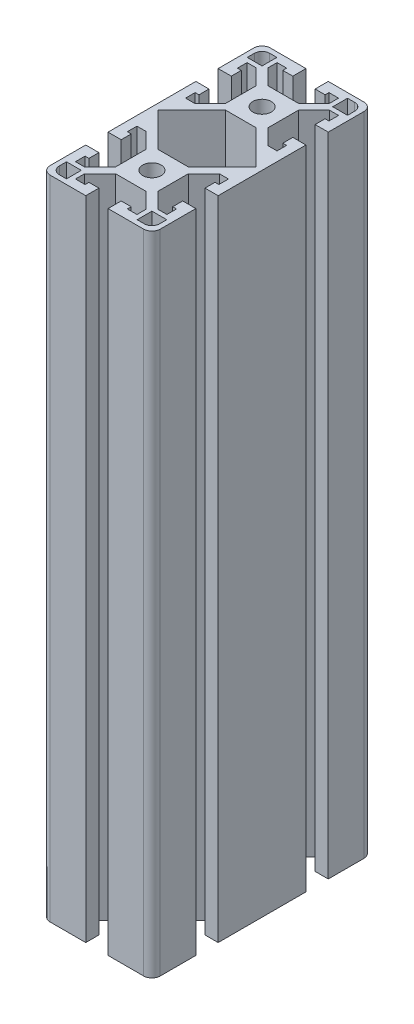
SolidWorks part; units mm, degrees
material "6063-T6"
ref_plane "Front Plane" through (0, 0, 0) normal (0, 0, 1) x (1, 0, 0)
ref_plane "Top Plane" through (0, 0, 0) normal (0, 1, 0) x (1, 0, 0)
ref_plane "Right Plane" through (0, 0, 0) normal (1, 0, 0) x (0, 0, -1)
sketch "Sketch1" plane through (0, 0, 0) normal (0, 0, 1) x (1, 0, 0)
  line L0 (0, 0) -> (0, 235)
  dimension "D1" = 235
other "40 series TS40-80LM-650037(1)"
ref_plane "Plane1" through (0, 0, 0) normal (0, 1, 0) x (-1, 0, 0)
sketch "Sketch2" plane through (0, 0, 0) normal (0, 1, 0) x (-1, 0, 0)
  line L2 (0, -27.681) -> (-5.5257, -27.681)
  line L3 (-5.5257, -27.681) -> (-11.176, -33.3313)
  line L4 (-7.6835, -36.6218) -> (-11.176, -36.6218)
  line L5 (-20, -37) -> (-20, -24.0488)
  line L6 (-4.0488, -40) -> (-17, -40)
  line L7 (-7.681, -20) -> (-7.681, -25.5257)
  line L8 (-7.681, -25.5257) -> (-13.3313, -31.176)
  line L9 (-16.6218, -31.176) -> (-16.6218, -27.6835)
  line L10 (-7.681, -14.4743) -> (-13.3313, -8.824)
  line L11 (-13.3313, -8.824) -> (-16.6218, -8.824)
  line L12 (-20, -24.0488) -> (-15.2248, -24.0488)
  line L13 (-20, 15.9512) -> (-20, -15.9512)
  line L14 (-5.5257, 12.319) -> (-17.8447, 0)
  line L15 (-5.5257, -12.319) -> (-17.8447, 0)
  line L16 (-7.681, -20) -> (-7.681, -14.4743)
  line L17 (-5.5257, -12.319) -> (0, -12.319)
  line L18 (7.681, -20) -> (7.681, -14.4743)
  line L19 (5.5257, -12.319) -> (17.8447, 0)
  line L20 (20, 15.9512) -> (15.2248, 15.9512)
  line L21 (4.0488, -35.2248) -> (7.6835, -35.2248)
  line L22 (7.681, 14.4743) -> (13.3313, 8.824)
  line L23 (7.6835, -36.6218) -> (7.6835, -35.2248)
  line L24 (4.0488, -35.2248) -> (4.0488, -40)
  line L25 (7.6835, -36.6218) -> (11.176, -36.6218)
  line L26 (11.176, -33.3313) -> (11.176, -36.6218)
  line L27 (7.681, -20) -> (7.681, -25.5257)
  line L28 (4.0488, -40) -> (17, -40)
  line L29 (20, -37) -> (20, -24.0488)
  line L30 (5.5257, -27.681) -> (11.176, -33.3313)
  line L31 (7.681, -25.5257) -> (13.3313, -31.176)
  line L32 (0, -12.319) -> (5.5257, -12.319)
  line L33 (0, -27.681) -> (5.5257, -27.681)
  line L35 (13.3313, 8.824) -> (16.6218, 8.824)
  line L36 (0, 12.319) -> (5.5257, 12.319)
  line L37 (-5.5257, 12.319) -> (0, 12.319)
  line L38 (16.6218, 8.824) -> (16.6218, 12.3165)
  line L39 (15.2248, 15.9512) -> (15.2248, 12.3165)
  line L40 (16.6218, 12.3165) -> (15.2248, 12.3165)
  line L41 (20, 24.0488) -> (15.2248, 24.0488)
  line L42 (0, 27.681) -> (5.5257, 27.681)
  line L43 (-4.0488, 40) -> (-17, 40)
  line L44 (-20, 37) -> (-20, 24.0488)
  line L45 (4.0488, 35.2248) -> (4.0488, 40)
  line L46 (16.6218, 31.176) -> (16.6218, 27.6835)
  line L47 (7.681, 20) -> (7.681, 25.5257)
  line L48 (13.3313, 31.176) -> (16.6218, 31.176)
  line L49 (15.2248, 24.0488) -> (15.2248, 27.6835)
  line L50 (7.681, 20) -> (7.681, 14.4743)
  line L51 (-7.681, 25.5257) -> (-7.681, 14.4743)
  line L52 (16.6218, 27.6835) -> (15.2248, 27.6835)
  line L53 (12.8372, 38.222) -> (12.8372, 32.8372)
  line L54 (20, 37) -> (20, 24.0488)
  line L55 (4.0488, 40) -> (17, 40)
  line L56 (12.8372, 38.222) -> (15.428, 38.222)
  line L57 (18.222, 35.428) -> (18.222, 32.8372)
  line L58 (12.8372, 32.8372) -> (18.222, 32.8372)
  line L59 (0, 27.681) -> (-5.5257, 27.681)
  line L60 (-4.0488, -35.2248) -> (-4.0488, -40)
  line L61 (-16.6218, -8.824) -> (-16.6218, -12.3165)
  line L62 (7.681, -14.4743) -> (13.3313, -8.824)
  line L63 (12.8372, -32.8372) -> (18.222, -32.8372)
  line L64 (20, 15.9512) -> (20, -15.9512)
  line L65 (7.681, 25.5257) -> (13.3313, 31.176)
  line L66 (5.5257, 27.681) -> (11.176, 33.3313)
  line L67 (5.5257, 12.319) -> (17.8447, 0)
  line L68 (-13.3313, -31.176) -> (-16.6218, -31.176)
  line L69 (-11.176, -33.3313) -> (-11.176, -36.6218)
  line L70 (-15.2248, -15.9512) -> (-15.2248, -12.3165)
  line L71 (-12.8372, -38.222) -> (-12.8372, -32.8372)
  line L72 (-12.8372, -38.222) -> (-15.428, -38.222)
  line L73 (-15.2248, -24.0488) -> (-15.2248, -27.6835)
  line L74 (-16.6218, -27.6835) -> (-15.2248, -27.6835)
  line L75 (-18.222, -35.428) -> (-18.222, -32.8372)
  line L76 (-12.8372, -32.8372) -> (-18.222, -32.8372)
  line L77 (-7.6835, -36.6218) -> (-7.6835, -35.2248)
  line L78 (-4.0488, -35.2248) -> (-7.6835, -35.2248)
  line L79 (-20, -15.9512) -> (-15.2248, -15.9512)
  line L80 (-16.6218, -12.3165) -> (-15.2248, -12.3165)
  line L81 (18.222, -35.428) -> (18.222, -32.8372)
  line L82 (12.8372, -38.222) -> (15.428, -38.222)
  line L83 (12.8372, -38.222) -> (12.8372, -32.8372)
  line L84 (16.6218, -12.3165) -> (15.2248, -12.3165)
  line L85 (20, -15.9512) -> (15.2248, -15.9512)
  line L86 (16.6218, -27.6835) -> (15.2248, -27.6835)
  line L87 (15.2248, -24.0488) -> (15.2248, -27.6835)
  line L88 (15.2248, -15.9512) -> (15.2248, -12.3165)
  line L89 (13.3313, -31.176) -> (16.6218, -31.176)
  line L90 (16.6218, -8.824) -> (16.6218, -12.3165)
  line L91 (20, -24.0488) -> (15.2248, -24.0488)
  line L92 (13.3313, -8.824) -> (16.6218, -8.824)
  line L93 (16.6218, -31.176) -> (16.6218, -27.6835)
  line L94 (11.176, 33.3313) -> (11.176, 36.6218)
  line L95 (7.6835, 36.6218) -> (11.176, 36.6218)
  line L96 (7.6835, 36.6218) -> (7.6835, 35.2248)
  line L97 (4.0488, 35.2248) -> (7.6835, 35.2248)
  line L98 (-4.0488, 35.2248) -> (-4.0488, 40)
  line L99 (-4.0488, 35.2248) -> (-7.6835, 35.2248)
  line L100 (-7.6835, 36.6218) -> (-7.6835, 35.2248)
  line L101 (-7.6835, 36.6218) -> (-11.176, 36.6218)
  line L102 (-11.176, 33.3313) -> (-11.176, 36.6218)
  line L103 (-5.5257, 27.681) -> (-11.176, 33.3313)
  line L104 (-18.222, 35.428) -> (-18.222, 32.8372)
  line L105 (-12.8372, 32.8372) -> (-18.222, 32.8372)
  line L106 (-7.681, 25.5257) -> (-13.3313, 31.176)
  line L107 (-13.3313, 31.176) -> (-16.6218, 31.176)
  line L108 (-16.6218, 31.176) -> (-16.6218, 27.6835)
  line L109 (-7.681, 14.4743) -> (-13.3313, 8.824)
  line L110 (-16.6218, 12.3165) -> (-15.2248, 12.3165)
  line L111 (-20, 15.9512) -> (-15.2248, 15.9512)
  line L112 (-15.2248, 15.9512) -> (-15.2248, 12.3165)
  line L113 (-16.6218, 8.824) -> (-16.6218, 12.3165)
  line L114 (-13.3313, 8.824) -> (-16.6218, 8.824)
  line L115 (-16.6218, 27.6835) -> (-15.2248, 27.6835)
  line L116 (-15.2248, 24.0488) -> (-15.2248, 27.6835)
  line L117 (-20, 24.0488) -> (-15.2248, 24.0488)
  line L118 (-12.8372, 38.222) -> (-15.428, 38.222)
  line L119 (-12.8372, 38.222) -> (-12.8372, 32.8372)
  arc A0 (-20, -37) -> (-17, -40) centre (-17, -37) ccw
  arc A1 (-20, 37) -> (-17, 40) centre (-17, 37) cw
  arc A2 (20, 37) -> (17, 40) centre (17, 37) ccw
  arc A3 (-15.428, -38.222) -> (-18.222, -35.428) centre (-15.428, -35.428) cw
  arc A4 (15.428, -38.222) -> (18.222, -35.428) centre (15.428, -35.428) ccw
  arc A5 (15.428, 38.222) -> (18.222, 35.428) centre (15.428, 35.428) cw
  arc A6 (-15.428, 38.222) -> (-18.222, 35.428) centre (-15.428, 35.428) ccw
  arc A7 (20, -37) -> (17, -40) centre (17, -37) cw
  circle A8 centre (0, -20) radius 3.35
  circle A9 centre (0, 20) radius 3.35
  point P1 (-20, 20)
  point P3 (-20, 40)
  point P34 (-20, 0)
  point P51 (20, 0)
  point P76 (0, 40)
  point P77 (20, 40)
  point P143 (20, 20)
  point P144 (20, -20)
  point P145 (-20, -20)
  point P146 (-20, -40)
  point P147 (0, -40)
  point P148 (20, -40)
  point P149 (0, 0)
  dimension "D1" = 6.7
hole_wizard "M8x1.25 Tapped Hole1" positions "Sketch3" profile "Sketch4" tap size "M8x1.25" standard "ANSI Metric"
sketch "Sketch3" plane through (0, 0, 0) normal (0, -1, 0) x (-1, 0, 0)
  point P0 (0, -20)
  point P3 (0, 20)
sketch "Sketch4" plane through (0, 0, 20) normal (1, 0, 0) x (0, 0, -1)
  line L0 (0, 0) -> (0, 27.0429)
  line L1 (0, 27.0429) -> (3.4, 25)
  line L2 (3.4, 25) -> (3.4, 0)
  line L5 (3.4, 0) -> (0, 0)
  line L10 (0, 27.0429) -> (-3.4, 25) construction
  line L11 (0, -6.35) -> (0, 107.95) construction
  dimension "Tap Drill Dia." = 6.8
  dimension "Tap Drill Depth" = 25
  dimension "Drill Angle" = 118
cosmetic thread "Hole Thread1" parameters "D1"=20, "D2"=8
cosmetic thread "Hole Thread2" parameters "D1"=20, "D2"=8
